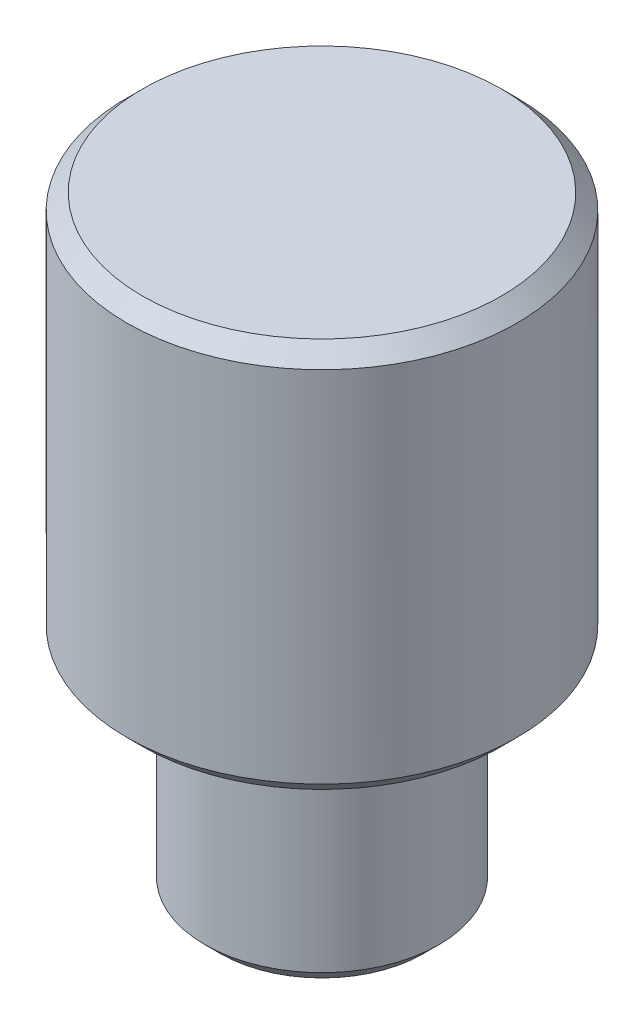
SolidWorks part; units mm, degrees
material "Plain Carbon Steel"
ref_plane "Front Plane" through (0, 0, 0) normal (0, 0, 1) x (1, 0, 0)
ref_plane "Top Plane" through (0, 0, 0) normal (0, 1, 0) x (1, 0, 0)
ref_plane "Right Plane" through (0, 0, 0) normal (1, 0, 0) x (0, 0, -1)
sketch "Sketch1" plane through (0, 0, 0) normal (0, 0, 1) x (1, 0, 0)
  line L0 (0, 0) -> (0, -100) construction
  line L1 (0, 0) -> (25, 0)
  line L2 (25, 0) -> (25, -50)
  line L3 (25, -50) -> (15, -50)
  line L4 (15, -50) -> (15, -78)
  line L5 (15, -78) -> (0, -78)
  line L6 (0, -78) -> (0, 0)
  dimension "D1" = 100
  dimension "D2" = 30
  dimension "D3" = 50
  dimension "D4" = 50
  dimension "D5" = 28
revolve "Revolve1" add sketch "Sketch1" angle 360 about L0
chamfer "Chamfer1" distance 2 angle 45 1 edges at (0, -78, 15)
cosmetic thread "Cosmetic Thread1" parameters "D1"=25, "D2"=27.797
chamfer "Chamfer2" distance 2 angle 45 2 edges at (0, -50, 25) (0, 0, 25)
